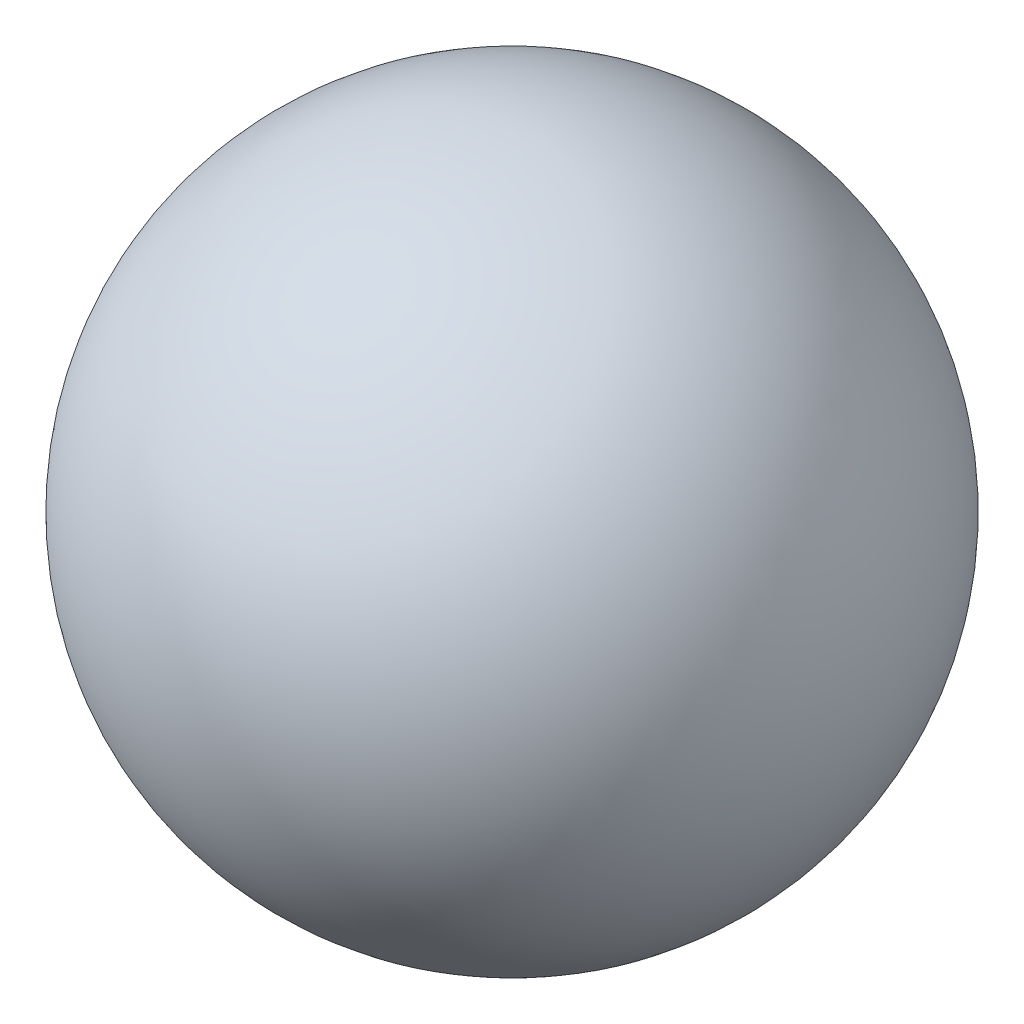
SolidWorks part; units mm, degrees
ref_plane "Front Plane" through (0, 0, 0) normal (0, 0, 1) x (1, 0, 0)
ref_plane "Top Plane" through (0, 0, 0) normal (0, 1, 0) x (1, 0, 0)
ref_plane "Right Plane" through (0, 0, 0) normal (1, 0, 0) x (0, 0, -1)
ref_axis "Axis1" through (0, 67.7, 0) along (0, -1, 0)
sketch "Sketch3" plane through (0, 0, 0) normal (0, 0, 1) x (1, 0, 0)
  line L0 (0, 67.7) -> (0, -42.3) construction
  line L1 (0, 12.7) -> (0, -12.7)
  arc A0 (0, 12.7) -> (0, -12.7) centre (0, 0) cw
  dimension "D1" = 25.4
revolve "trackball" add sketch "Sketch3" angle 360 about axis through (0, 67.7, 0) along (0, -1, 0)
